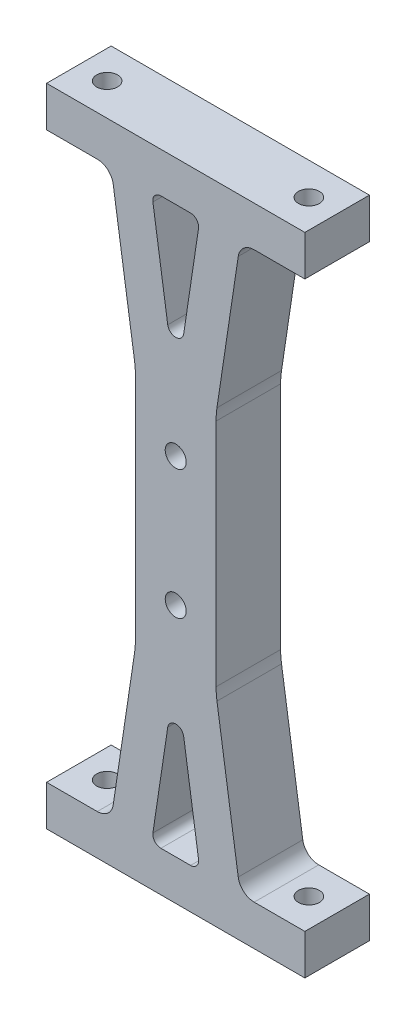
SolidWorks part; units mm, degrees
ref_plane "Front Plane" through (0, 0, 0) normal (1, 0, 0) x (0, 1, 0)
ref_plane "Top Plane" through (0, 0, 0) normal (0, 0, 1) x (0, 1, 0)
ref_plane "Right Plane" through (0, 0, 0) normal (0, 1, 0) x (-1, 0, 0)
sketch "Sketch1" plane through (0, 0, 0) normal (0, 0, 1) x (0, 1, 0)
  line L0 (-56.3235, 20.6324) -> (-56.3235, -11.3676)
  line L1 (-56.3235, -11.3676) -> (-51.3235, -11.3676)
  line L2 (-51.3235, -11.3676) -> (-51.3235, -3.3676)
  line L3 (-51.3235, -3.3676) -> (-31.3235, -0.3676)
  line L4 (-31.3235, -0.3676) -> (-1.3235, -0.3676)
  line L5 (-1.3235, -0.3676) -> (18.6765, -3.3676)
  line L6 (18.6765, -3.3676) -> (18.6765, -11.3676)
  line L7 (18.6765, -11.3676) -> (23.6765, -11.3676)
  line L8 (23.6765, -11.3676) -> (23.6765, 20.6324)
  line L9 (23.6765, 20.6324) -> (18.6765, 20.6324)
  line L10 (18.6765, 20.6324) -> (18.6765, 12.6324)
  line L11 (18.6765, 12.6324) -> (-1.3235, 9.6324)
  line L12 (-1.3235, 9.6324) -> (-31.3235, 9.6324)
  line L14 (-51.3235, 20.6324) -> (-56.3235, 20.6324)
  line L15 (-31.3235, 9.6324) -> (-51.3235, 12.6324)
  line L16 (-51.3235, 12.6324) -> (-51.3235, 20.6324)
  line L17 (-16.3235, 9.6324) -> (-16.3235, -0.3676) construction
  point P2 (-16.3235, 4.6324)
  point P17 (-56.3235, 4.6324)
  dimension "D1" = 5
  dimension "D2" = 32
  dimension "D3" = 10
  dimension "D4" = 5
  dimension "D5" = 80
  dimension "D6" = 20
  dimension "D7" = 20
  dimension "D8" = 8
  dimension "D9" = 8
extrude "Boss-Extrude1" add sketch "Sketch1" along normal blind 8
sketch "Sketch2" plane through (0, 0, 8) normal (0, 0, 1) x (1, 0, 0)
  line L0 (-9.6324, -16.3235) -> (0.3676, -16.3235) construction
  line L1 (-9.6324, -1.3235) -> (-9.6324, -31.3235) construction
  line L2 (0.3676, -31.3235) -> (0.3676, -1.3235) construction
  line L6 (-7.6324, -51.3235) -> (-4.6324, -31.3235)
  line L7 (-4.6324, -31.3235) -> (-1.6324, -51.3235)
  line L8 (-1.6324, -51.3235) -> (-7.6324, -51.3235)
  line L11 (-12.6324, -51.3235) -> (-20.6324, -51.3235) construction
  line L14 (-1.6324, 18.6765) -> (-7.6324, 18.6765)
  line L15 (-4.6324, -1.3235) -> (-1.6324, 18.6765)
  line L16 (-7.6324, 18.6765) -> (-4.6324, -1.3235)
  line L17 (-9.6324, -31.3235) -> (-12.6324, -51.3235) construction
  point P8 (-4.6324, -51.3235)
  point P10 (-4.6324, -16.3235)
  dimension "D1" = 0
extrude "Cut-Extrude1" cut sketch "Sketch2" against normal up to next
sketch "Sketch3" plane through (0, -56.3235, 0) normal (0, -1, 0) x (1, 0, 0)
  line L0 (-20.6324, 4) -> (11.3676, 4) construction
  line L1 (-20.6324, 8) -> (-20.6324, 0) construction
  line L2 (11.3676, 8) -> (11.3676, 0) construction
  line L3 (-17.1324, 4) -> (7.8676, 4) construction
  circle A0 centre (-17.1324, 4) radius 1.3
  circle A1 centre (7.8676, 4) radius 1.3
  point P10 (-4.6324, 4)
  point P11 (-4.6324, 4)
  dimension "D2" = 2.6
  dimension "D1" = 25
extrude "Cut-Extrude2" cut sketch "Sketch3" against normal through all
fillet "Fillet6" radius 2 4 edges at (-12.6324, 18.6765, 4) (3.3676, 18.6765, 4) (3.3676, -51.3235, 4) (-12.6324, -51.3235, 4)
fillet "Fillet7" radius 1 6 edges at (-7.6324, 18.6765, 4) (-1.6324, 18.6765, 4) (-4.6324, -1.3235, 4) (-1.6324, -51.3235, 4) (-7.6324, -51.3235, 4) (-4.6324, -31.3235, 4)
fillet "Fillet8" radius 10 4 edges at (0.3676, -1.3235, 4) (-9.6324, -1.3235, 4) (-9.6324, -31.3235, 4) (0.3676, -31.3235, 4)
sketch "Sketch4" plane through (0, 0, 8) normal (0, 0, 1) x (1, 0, 0)
  line L0 (-9.6324, -16.3235) -> (0.3676, -16.3235) construction
  line L1 (-9.6324, -2.0694) -> (-9.6324, -30.5777) construction
  line L2 (0.3676, -30.5777) -> (0.3676, -2.0694) construction
  line L3 (-4.6324, 4.4177) -> (-4.6324, -37.0648) construction
  arc A0 (-5.6213, 5.2694) -> (-3.6434, 5.2694) centre (-4.6324, 5.4177) ccw construction
  arc A1 (-3.6434, -37.9164) -> (-5.6213, -37.9164) centre (-4.6324, -38.0648) ccw construction
  circle A2 centre (-4.6324, -8.3235) radius 1.3
  circle A3 centre (-4.6324, -24.3235) radius 1.3
  dimension "D1" = 2.6
  dimension "D2" = 8
extrude "Cut-Extrude3" cut sketch "Sketch4" against normal up to next
